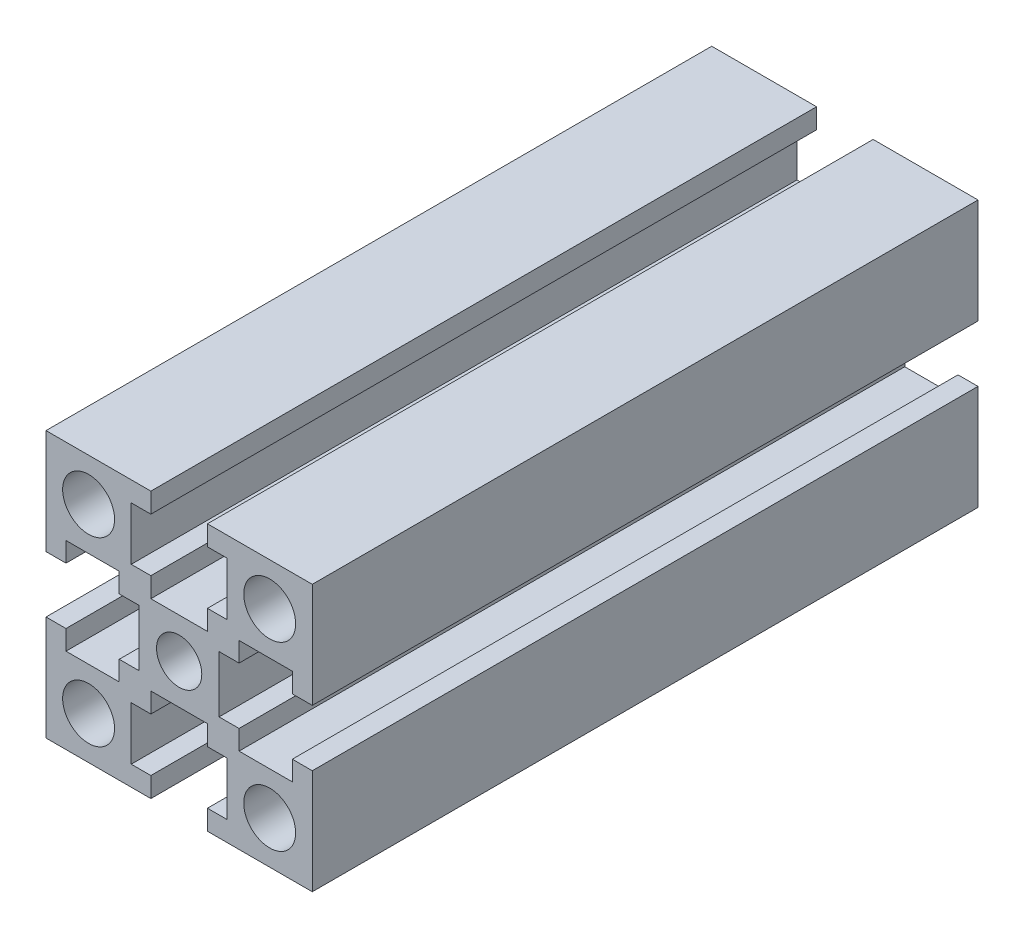
SolidWorks part; units mm, degrees
ref_plane "前视基准面" through (0, 0, 0) normal (0, 0, 1) x (1, 0, 0)
ref_plane "上视基准面" through (0, 0, 0) normal (0, 1, 0) x (1, 0, 0)
ref_plane "右视基准面" through (0, 0, 0) normal (1, 0, 0) x (0, 0, -1)
sketch "草图1" plane through (0, 0, 0) normal (0, 0, 1) x (1, 0, 0)
  line L0 (-5.3384, 19.5458) -> (-21.0884, 19.5458)
  line L1 (-21.0884, 19.5458) -> (-21.0884, 3.7958)
  line L2 (-5.3384, 16.5458) -> (-8.2884, 16.5458)
  line L3 (-18.0884, 6.7458) -> (-18.0884, 3.7958)
  line L4 (-7.0884, 3.7958) -> (-7.0884, -4.7042)
  line L5 (-5.3384, -6.4542) -> (3.1616, -6.4542)
  line L6 (4.9116, -4.7042) -> (4.9116, 3.7958)
  line L7 (3.1616, 5.5458) -> (-5.3384, 5.5458)
  line L8 (-10.0884, 6.7458) -> (-10.0884, 3.7958)
  line L9 (-5.3384, 8.5458) -> (-8.2884, 8.5458)
  line L10 (-18.0884, 6.7458) -> (-10.0884, 6.7458)
  line L11 (-21.0884, 3.7958) -> (-18.0884, 3.7958)
  line L12 (-10.0884, 3.7958) -> (-7.0884, 3.7958)
  line L13 (-8.2884, 16.5458) -> (-8.2884, 8.5458)
  line L14 (-5.3384, 19.5458) -> (-5.3384, 16.5458)
  line L15 (-5.3384, 8.5458) -> (-5.3384, 5.5458)
  line L16 (3.1616, 19.5458) -> (18.9116, 19.5458)
  line L17 (18.9116, 19.5458) -> (18.9116, 3.7958)
  line L18 (3.1616, 16.5458) -> (6.1116, 16.5458)
  line L19 (15.9116, 6.7458) -> (15.9116, 3.7958)
  line L20 (7.9116, 6.7458) -> (7.9116, 3.7958)
  line L21 (3.1616, 8.5458) -> (6.1116, 8.5458)
  line L22 (15.9116, 6.7458) -> (7.9116, 6.7458)
  line L23 (18.9116, 3.7958) -> (15.9116, 3.7958)
  line L24 (7.9116, 3.7958) -> (4.9116, 3.7958)
  line L25 (6.1116, 16.5458) -> (6.1116, 8.5458)
  line L26 (3.1616, 19.5458) -> (3.1616, 16.5458)
  line L27 (3.1616, 8.5458) -> (3.1616, 5.5458)
  line L28 (-5.3384, -20.4542) -> (-21.0884, -20.4542)
  line L29 (-21.0884, -20.4542) -> (-21.0884, -4.7042)
  line L30 (-5.3384, -17.4542) -> (-8.2884, -17.4542)
  line L31 (-18.0884, -7.6542) -> (-18.0884, -4.7042)
  line L32 (-10.0884, -7.6542) -> (-10.0884, -4.7042)
  line L33 (-5.3384, -9.4542) -> (-8.2884, -9.4542)
  line L34 (-18.0884, -7.6542) -> (-10.0884, -7.6542)
  line L35 (-21.0884, -4.7042) -> (-18.0884, -4.7042)
  line L36 (-10.0884, -4.7042) -> (-7.0884, -4.7042)
  line L37 (-8.2884, -17.4542) -> (-8.2884, -9.4542)
  line L38 (-5.3384, -20.4542) -> (-5.3384, -17.4542)
  line L39 (-5.3384, -9.4542) -> (-5.3384, -6.4542)
  line L40 (3.1616, -20.4542) -> (18.9116, -20.4542)
  line L41 (18.9116, -20.4542) -> (18.9116, -4.7042)
  line L42 (3.1616, -17.4542) -> (6.1116, -17.4542)
  line L43 (15.9116, -7.6542) -> (15.9116, -4.7042)
  line L44 (7.9116, -7.6542) -> (7.9116, -4.7042)
  line L45 (3.1616, -9.4542) -> (6.1116, -9.4542)
  line L46 (15.9116, -7.6542) -> (7.9116, -7.6542)
  line L47 (18.9116, -4.7042) -> (15.9116, -4.7042)
  line L48 (7.9116, -4.7042) -> (4.9116, -4.7042)
  line L49 (6.1116, -17.4542) -> (6.1116, -9.4542)
  line L50 (3.1616, -20.4542) -> (3.1616, -17.4542)
  line L51 (3.1616, -9.4542) -> (3.1616, -6.4542)
  circle A0 centre (-14.6884, 13.1458) radius 3.9
  circle A1 centre (12.5116, 13.1458) radius 3.9
  circle A2 centre (-14.6884, -14.0542) radius 3.9
  circle A3 centre (12.5116, -14.0542) radius 3.9
  circle A4 centre (-1.0884, -0.4542) radius 3.4
extrude "凸台-拉伸1" add sketch "草图1" along normal blind 100
